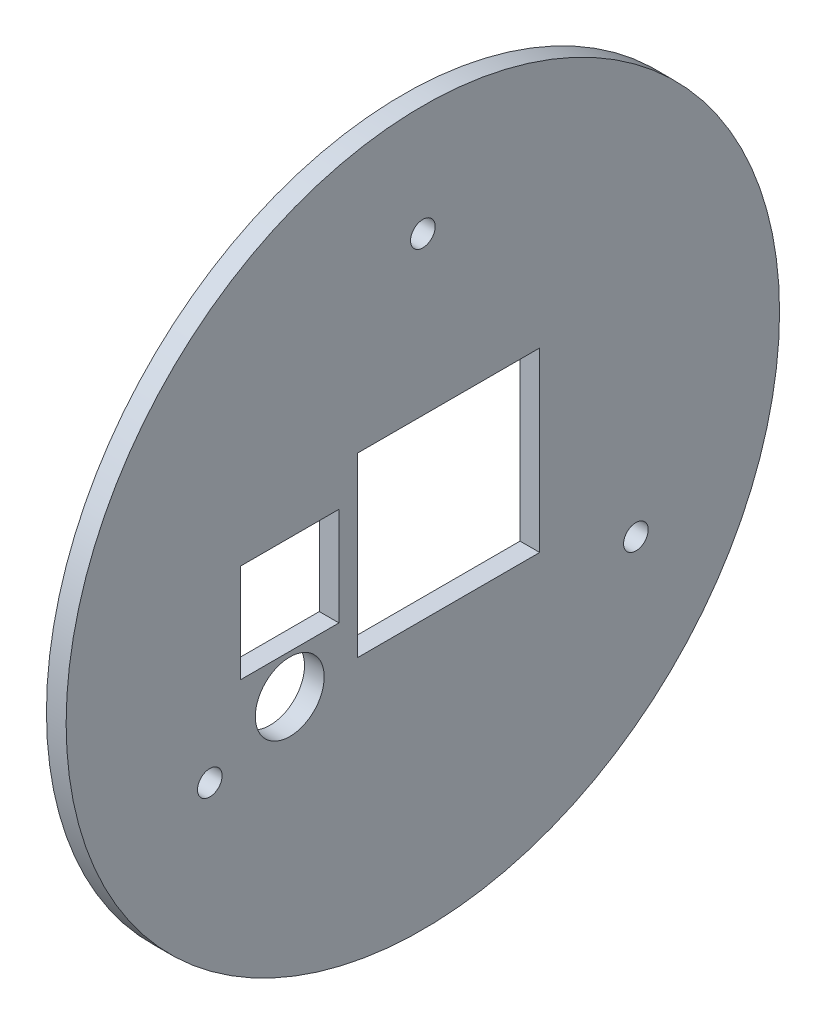
SolidWorks part; units mm, degrees
ref_plane "Front Plane" through (0, 0, 0) normal (0, 0, 1) x (1, 0, 0)
ref_plane "Top Plane" through (0, 0, 0) normal (0, 1, 0) x (1, 0, 0)
ref_plane "Right Plane" through (0, 0, 0) normal (1, 0, 0) x (0, 0, -1)
sketch "Sketch1" plane through (0, 0, 0) normal (1, 0, 0) x (0, 0, -1)
  line L0 (-72.5, 0) -> (72.5, 0) construction
  line L1 (-13.2483, 18) -> (23.7517, 18)
  line L2 (-13.2483, 18) -> (-13.2483, -18)
  line L3 (-13.2483, -18) -> (23.7517, -18)
  line L4 (23.7517, 18) -> (23.7517, -18)
  line L5 (4.2715, -18) -> (-70.23, -18) construction
  line L6 (-27.0483, -18) -> (-27.0483, 67.2654) construction
  line L7 (-37.0483, 10) -> (-17.0483, 10)
  line L8 (-37.0483, 10) -> (-37.0483, -10)
  line L9 (-37.0483, -10) -> (-17.0483, -10)
  line L10 (-17.0483, 10) -> (-17.0483, -10)
  line L11 (0, 72.5) -> (0, -72.5) construction
  circle A0 centre (0, 0) radius 72.5
  circle A1 centre (-27.0483, -18) radius 7
  circle A2 centre (0, 50) radius 2.5
  circle A3 centre (43.3013, -25) radius 2.5
  circle A4 centre (-43.3013, -25) radius 2.5
  point P13 (0, 0)
  dimension "D1" = 145
  dimension "D2" = 37
  dimension "D3" = 5
  dimension "D7" = 14
  dimension "D4" = 50
  dimension "D6" = 36
  dimension "D8" = 13.8
  dimension "D9" = 20
  dimension "D10" = 20
  dimension "D11" = 8
  dimension "D5" = 3
extrude "Boss-Extrude1" add sketch "Sketch1" along normal blind 4
